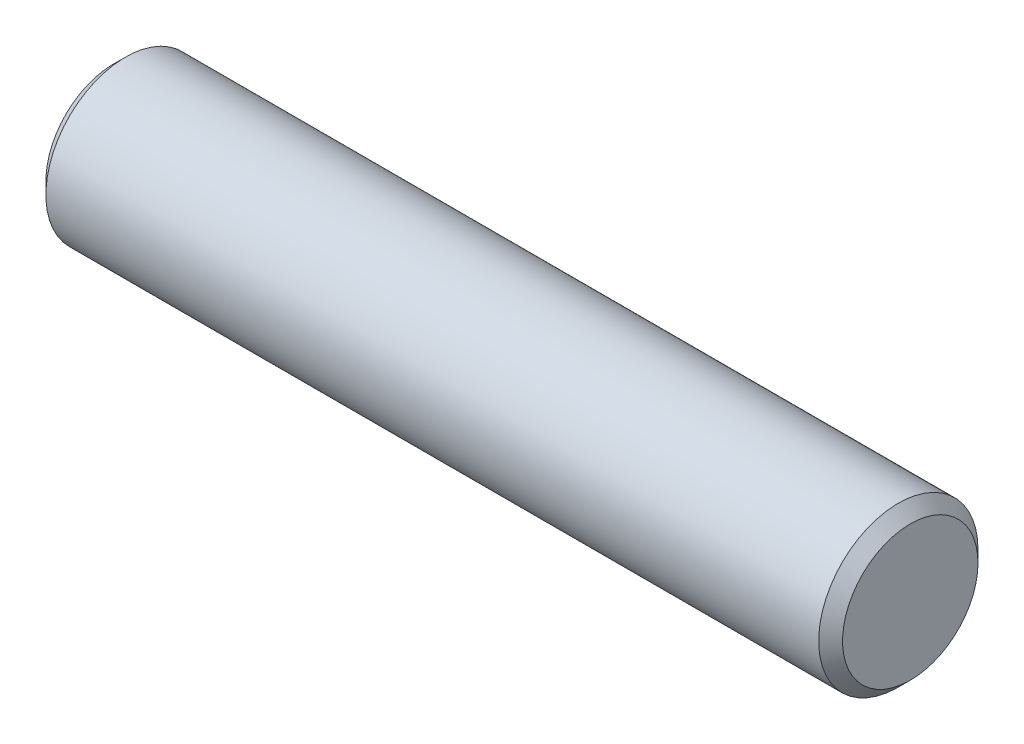
SolidWorks part; units mm, degrees
revolve "BaseBody" add sketch "BodySke" angle 360 about L14
sketch "BodySke" plane through (0, 0, 0) normal (0, 0, 1) x (1, 0, 0)
  line L0 (83, 15.875) -> (83, -6.35) construction
  line L1 (2.5, 15.875) -> (2.5, -3.175) construction
  line L2 (95, 6.35) -> (95, 3.175) construction
  line L10 (0, 10) -> (100, 10)
  line L12 (100, 10) -> (100, 0)
  line L13 (100, 0) -> (0, 0)
  line L14 (-3.175, 0) -> (107.95, 0) construction
  line L18 (0, 10) -> (0, 0)
  dimension "Diameter" = 20
  dimension "Length" = 100
  dimension "Advance" = 2.5
  dimension "Minor_dia" = 17
  dimension "Thread_max" = 95
cosmetic thread "ThreadCosmetic" [suppressed] parameters "Thread_minor"=17
ref_plane "Plane1" through (0, 0, 0) normal (0, 0, 1) x (1, 0, 0)
ref_plane "Plane2" through (0, 0, 0) normal (0, 1, 0) x (1, 0, 0)
ref_plane "Plane3" through (0, 0, 0) normal (1, 0, 0) x (0, 0, -1)
chamfer "Chamfer1" distance 1.5 angle 45 2 edges at (100, 0, 10) (0, 0, 10)
sketch "ThdSchSke" plane through (0, 0, 0) normal (0, 0, 1) x (1, 0, 0)
  line L0 (1.0503, -8.5) -> (0, -10)
  line L1 (1.0503, -8.5) -> (2.1006, -10)
  line L2 (2.1006, -10) -> (2.1006, -12.5)
  line L3 (-3.175, 0) -> (5.1513, 0) construction
  line L4 (0, 10) -> (0, -10) construction
  line L5 (2.1006, -12.5) -> (0, -12.5)
  line L6 (0, -12.5) -> (0, -10)
  dimension "Thread_minor" = 17
  dimension "Diameter" = 20
revolve "ThreadSchematic" [suppressed] cut sketch "ThdSchSke" angle 360 about L3
pattern_linear "ThdSchPat" [suppressed]
equation "\"Thread_minor@ThreadCosmetic\" = \"Minor_dia@BodySke\""
equation "\"Chamfer@Chamfer1\" =  ( \"Diameter@BodySke\" - \"Minor_dia@BodySke\" ) / 2"
equation "\"Thread_minor@ThdSchSke\" = \"Minor_dia@BodySke\""
equation "\"Diameter@ThdSchSke\" = \"Diameter@BodySke\""
equation "\"Overcut@ThdSchSke\" = \"Diameter@BodySke\" * 1.25"
equation "\"Num_threads@ThdSchPat\" = int( (\"Thread_max@BodySke\" - \"Advance@BodySke\" ) / \"Advance@BodySke\" + 0.999 ) + 1"
equation "\"Advance@ThdSchPat\" = \"Thread_max@BodySke\" /  ( \"Num_threads@ThdSchPat\" - 1 ) 'relax it"
equation "\"Num_threads@ThdSchPat\" = \"Num_threads@ThdSchPat\" - sgn( \"Num_threads@ThdSchPat\" - 1 ) '---chamfered tips only---"
